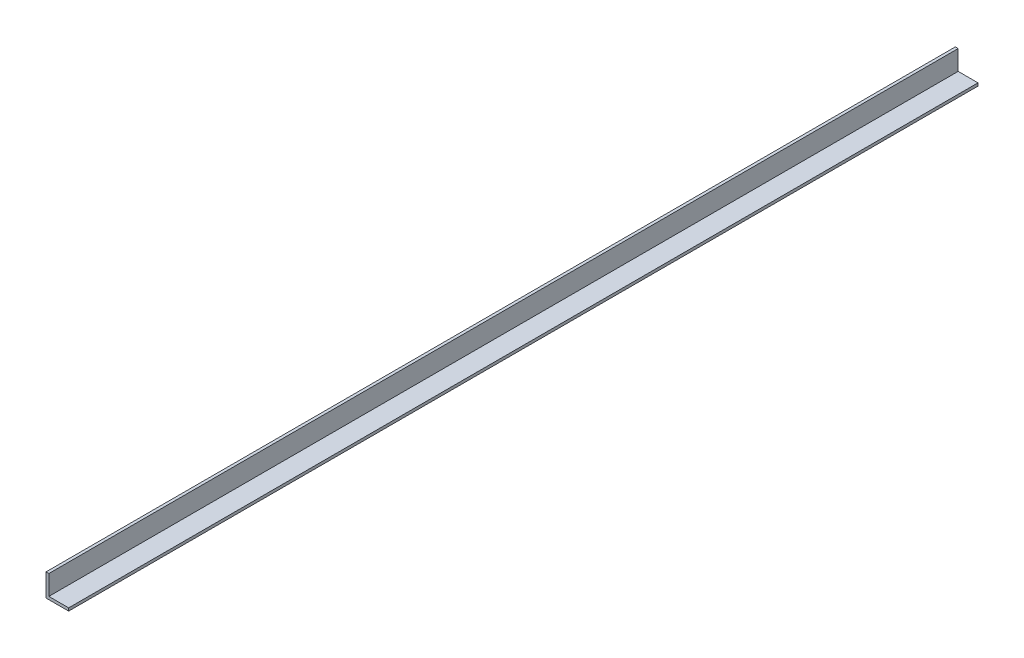
SolidWorks part; units mm, degrees
material "ASTM A36 Acero"
ref_plane "Alzado" through (0, 0, 0) normal (0, 0, 1) x (1, 0, 0)
ref_plane "Planta" through (0, 0, 0) normal (0, 1, 0) x (1, 0, 0)
ref_plane "Vista lateral" through (0, 0, 0) normal (1, 0, 0) x (0, 0, -1)
sketch "Croquis1" plane through (0, 0, 0) normal (0, 0, 1) x (1, 0, 0)
  line L0 (0, 152) -> (0, 0)
  line L1 (0, 0) -> (152, 0)
  line L2 (152, 0) -> (152, 19.05)
  line L3 (152, 19.05) -> (19.05, 19.05)
  line L4 (19.05, 19.05) -> (19.05, 152)
  line L5 (19.05, 152) -> (0, 152)
  dimension "D1" = 19.05
  dimension "D2" = 152
extrude "Saliente-Extruir1" add sketch "Croquis1" against normal blind 6100
